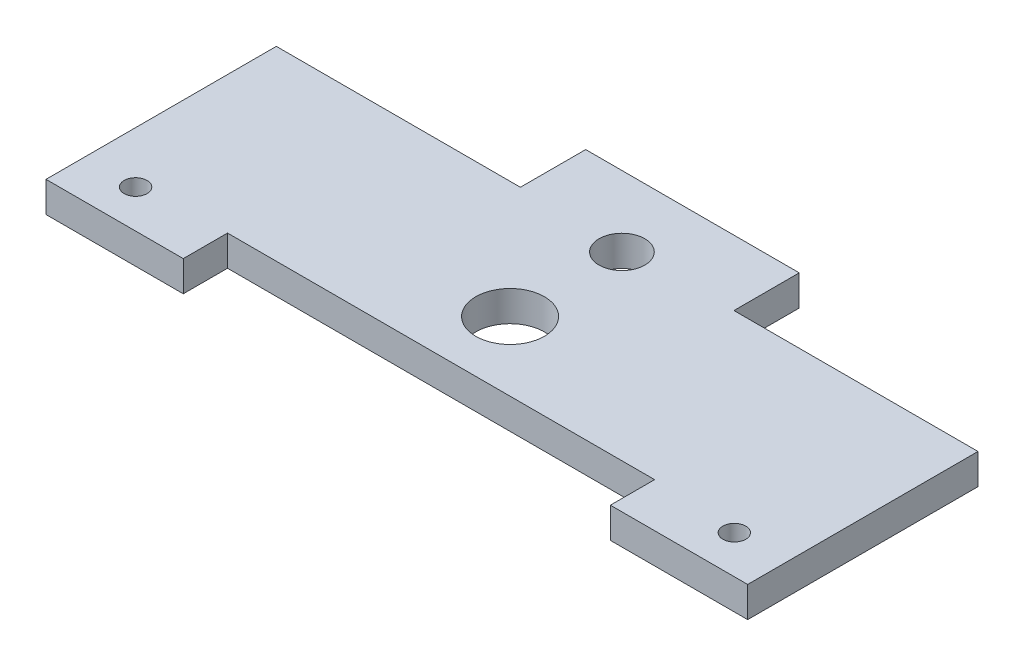
SolidWorks part; units mm, degrees
material "Thornel Mat VMA"
ref_plane "Front" through (0, 0, 0) normal (0, 0, 1) x (1, 0, 0)
ref_plane "Top" through (0, 0, 0) normal (0, 1, 0) x (1, 0, 0)
ref_plane "Right" through (0, 0, 0) normal (1, 0, 0) x (0, 0, -1)
sketch "Sketch1" plane through (0, 0, 0) normal (0, 1, 0) x (1, 0, 0)
  line L1 (-14, 47.0643) -> (14, 47.0643)
  line L2 (7, 59.265) -> (23, 59.265)
  line L4 (-23, 44.1643) -> (-23, 59.265)
  line L6 (-23, 59.265) -> (-7, 59.265)
  line L7 (14, 44.1643) -> (23, 44.1643)
  line L8 (-7, 63.5457) -> (-7, 59.265)
  line L10 (7, 63.5457) -> (7, 59.265)
  line L11 (-23, 44.1643) -> (-14, 44.1643)
  line L12 (-7, 63.5457) -> (7, 63.5457)
  line L14 (23, 59.265) -> (23, 44.1643)
  line L15 (0, 63.5457) -> (0, 0) construction
  line L16 (0, 0) -> (25.051, 0) construction
  line L17 (-19.625, 46.6643) -> (19.625, 46.6643) construction
  line L18 (14, 44.1643) -> (14, 47.0643)
  line L19 (-14, 44.1643) -> (-14, 47.0643)
  circle A1 centre (0, 58.9222) radius 1.5
  circle A3 centre (19.625, 46.6643) radius 0.75
  circle A5 centre (-19.625, 46.6643) radius 0.75
  circle A8 centre (0, 51.5893) radius 2.25
  dimension "D6" = 15.1007
  dimension "D4" = 63.5457
  dimension "D9" = 2.9
  dimension "D3" = 4.5
  dimension "D1" = 3
  dimension "D13" = 1.5
  dimension "D2" = 7.3329
  dimension "D5" = 4.2807
  dimension "D7" = 14
  dimension "D8" = 46
  dimension "D10" = 28
  dimension "D11" = 2.5
  dimension "D12" = 39.25
  dimension "D14" = 4.6235
extrude "Boss-Extrude1" add sketch "Sketch1" along normal blind 2 contours L12 L10 L2 L14 L1 L4 L6 L8
sketch "Sketch2" plane through (0, 2, 0) normal (0, 1, 0) x (1, 0, 0)
  line L8 (-23, 59.265) -> (-23, 44.1643)
  line L9 (-14, 47.0643) -> (14, 47.0643)
  line L10 (23, 44.1643) -> (23, 59.265)
  line L11 (23, 59.265) -> (7, 59.265)
  line L12 (7, 59.265) -> (7, 63.5457)
  line L13 (7, 63.5457) -> (-7, 63.5457)
  line L14 (-7, 63.5457) -> (-7, 59.265)
  line L15 (-7, 59.265) -> (-23, 59.265)
  line L16 (-23, 59.265) -> (-23, 44.1643)
  line L17 (-14, 47.0643) -> (14, 47.0643)
  line L18 (23, 44.1643) -> (23, 59.265)
  line L19 (23, 59.265) -> (7, 59.265)
  line L20 (7, 59.265) -> (7, 63.5457)
  line L21 (7, 63.5457) -> (-7, 63.5457)
  line L22 (-7, 63.5457) -> (-7, 59.265)
  line L23 (-7, 59.265) -> (-23, 59.265)
  line L28 (-23, 44.1643) -> (-14, 44.1643)
  line L29 (-23, 44.1643) -> (-14, 44.1643)
  line L30 (-14, 44.1643) -> (-14, 47.0643)
  line L31 (-14, 44.1643) -> (-14, 47.0643)
  line L32 (14, 47.0643) -> (14, 44.1643)
  line L33 (14, 47.0643) -> (14, 44.1643)
  line L34 (14, 44.1643) -> (23, 44.1643)
  line L35 (14, 44.1643) -> (23, 44.1643)
  circle A0 centre (0, 51.5893) radius 2.25 construction
  circle A1 centre (-19.625, 46.6643) radius 0.75
  circle A2 centre (0, 51.5893) radius 0.75
  circle A3 centre (19.625, 46.6643) radius 0.75
  circle A4 centre (0, 58.9222) radius 0.75
  dimension "D2" = 1.5
  dimension "D1" = 0
extrude "Boss-Extrude2" [suppressed] add sketch "Sketch2" along normal blind 1 separate body
